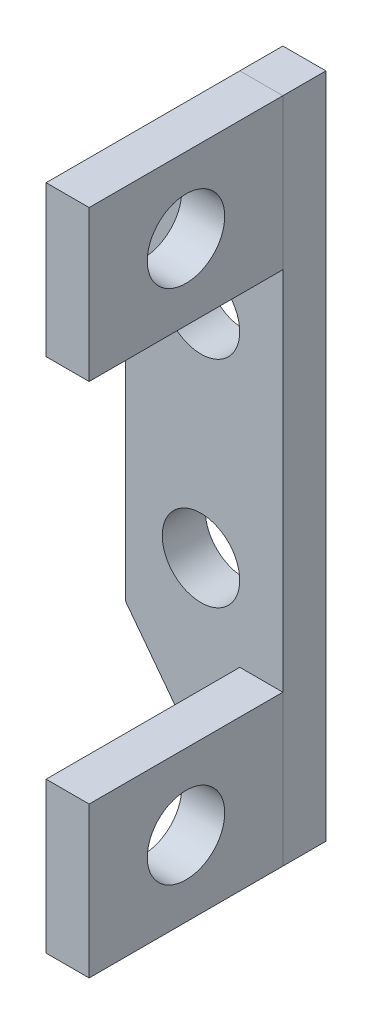
SolidWorks part; units mm, degrees
ref_plane "Front Plane" through (0, 0, 0) normal (0, 0, 1) x (1, 0, 0)
ref_plane "Top Plane" through (0, 0, 0) normal (0, 1, 0) x (1, 0, 0)
ref_plane "Right Plane" through (0, 0, 0) normal (1, 0, 0) x (0, 0, -1)
sketch "Sketch2" plane through (0, 0, 0) normal (0, 0, 1) x (1, 0, 0)
  line L0 (-10, 226.4206) -> (-10, 176.4206) construction
  line L1 (-10, 196.9206) -> (-2.6956, 196.9206)
  line L2 (-10, 196.9206) -> (-10, 213.9206)
  line L3 (-10, 213.9206) -> (-2.6956, 213.9206)
  line L4 (-2.6956, 196.9206) -> (-2.6956, 213.9206)
  line L5 (-2.4956, 220.74) -> (-2.4956, 195.8582) construction
  line L6 (-6.5, 200.4206) -> (-10, 200.4206) construction
  line L7 (-6.5, 200.4206) -> (-6.5, 196.9206) construction
  line L8 (-10, 205.4206) -> (-2.6956, 205.4206) construction
  line L9 (-6.5, 200.4206) -> (-6.5, 210.4206) construction
  line L10 (-2.6956, 196.9206) -> (-2.6956, 189.9206)
  line L11 (-2.6956, 189.9206) -> (-4.6956, 189.9206)
  line L12 (-4.6956, 189.9206) -> (-10, 196.9206)
  line L13 (-2.6956, 213.9206) -> (-2.6956, 220.9206)
  line L14 (-2.6956, 220.9206) -> (-4.6956, 220.9206)
  line L15 (-4.6956, 220.9206) -> (-10, 213.9206)
  circle A0 centre (-6.5, 200.4206) radius 1.75 construction
  circle A1 centre (-6.5, 200.4206) radius 1.75 construction
  point P15 (-6.5, 205.4206)
  dimension "D1" = 0.2
  dimension "D2" = 7
  dimension "D3" = 2
extrude "Boss-Extrude1" add sketch "Sketch2" along normal blind 2 contours L12 L11 L10 L1 | L14 L15 L3 L13 | L1 L4 L3 L2
sketch "Sketch5" plane through (0, 0, 2) normal (0, 0, 1) x (1, 0, 0)
  point P0 (-6.5, 200.4206)
  point P3 (-6.5, 210.4206)
hole_wizard "M3 Clearance Hole1" positions "Sketch5" profile "Sketch4" hole size "M3" standard "ANSI Metric" end condition through all
sketch "Sketch4" plane through (-6.5, 200.4206, 2) normal (1, 0, 0) x (0, -1, 0)
  line L0 (0, 0) -> (0, 2)
  line L1 (0, 2) -> (1.8, 2)
  line L2 (1.8, 2) -> (1.8, 0)
  line L5 (1.8, 0) -> (0, 0)
  line L11 (0, -6.35) -> (0, 107.95) construction
  dimension "Thru Hole Dia." = 3.6
  dimension "Thru Hole Depth" = 2
sketch "Sketch6" plane through (0, 0, 2) normal (0, 0, 1) x (1, 0, 0)
  line L0 (-10, 205.4206) -> (-2.6956, 205.4206) construction
  line L1 (-2.6956, 213.9206) -> (-4.6956, 213.9206)
  line L2 (-2.6956, 213.9206) -> (-2.6956, 220.9206)
  line L3 (-2.6956, 220.9206) -> (-4.6956, 220.9206)
  line L4 (-4.6956, 213.9206) -> (-4.6956, 220.9206)
  line L7 (-2.6956, 189.9206) -> (-4.6956, 189.9206)
  line L8 (-4.6956, 196.9206) -> (-4.6956, 189.9206)
  line L9 (-2.6956, 196.9206) -> (-4.6956, 196.9206)
  line L10 (-2.6956, 196.9206) -> (-2.6956, 189.9206)
  line L12 (-2.6956, 220.9206) -> (-2.6956, 189.9206) construction
  line L13 (-10, 196.9206) -> (-10, 213.9206) construction
  line L14 (-2.6956, 220.9206) -> (-4.6956, 220.9206) construction
  dimension "D1" = 7
  dimension "D2" = 2
extrude "Boss-Extrude2" add sketch "Sketch6" along normal blind 9 separate body
sketch "Sketch7" plane through (-4.6956, 0, 0) normal (-1, 0, 0) x (0, 0, 1)
  point P0 (6.5, 193.4206)
  point P2 (6.5, 217.4206)
hole_wizard "M3 Clearance Hole2" positions "Sketch7" profile "Sketch8" hole size "M3" standard "ANSI Metric" end condition through all
sketch "Sketch8" plane through (-4.6956, 193.4206, 6.5) normal (0, 1, 0) x (0, 0, 1)
  line L0 (0, 0) -> (0, 2)
  line L1 (0, 2) -> (1.8, 2)
  line L2 (1.8, 2) -> (1.8, 0)
  line L5 (1.8, 0) -> (0, 0)
  line L11 (0, -6.35) -> (0, 107.95) construction
  dimension "Thru Hole Dia." = 3.6
  dimension "Thru Hole Depth" = 2
